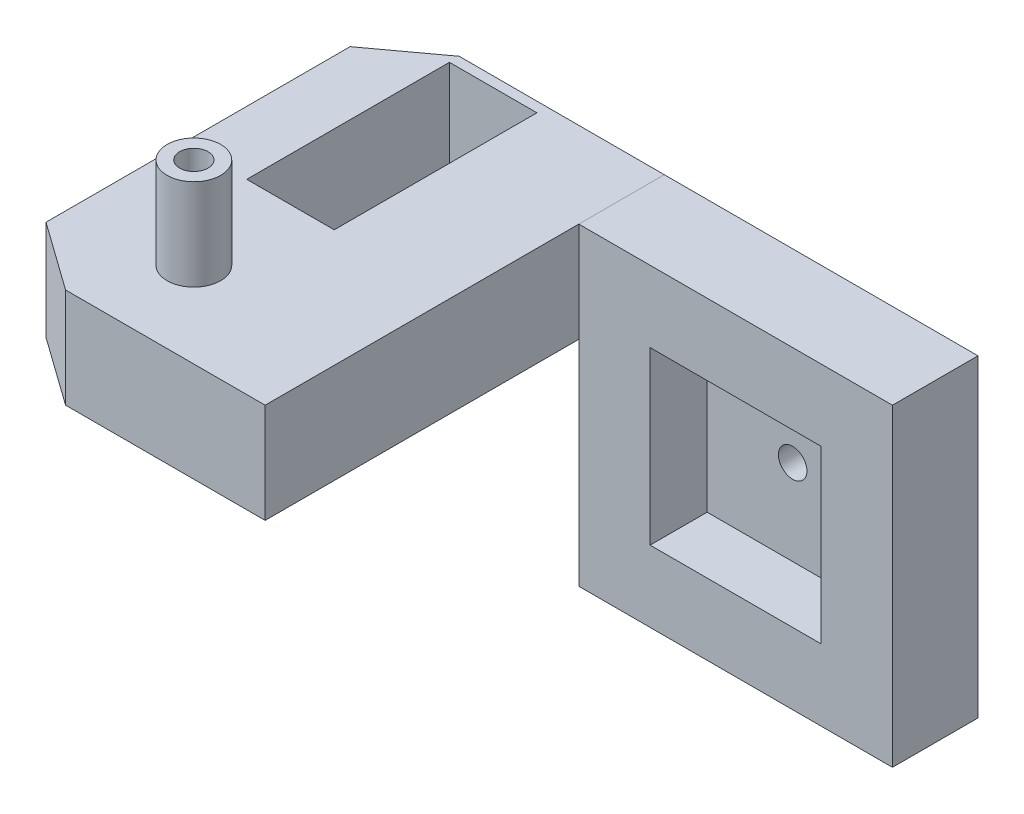
SolidWorks part; units mm, degrees
ref_plane "Front Plane" through (0, 0, 0) normal (0, 0, 1) x (1, 0, 0)
ref_plane "Top Plane" through (0, 0, 0) normal (0, 1, 0) x (1, 0, 0)
ref_plane "Right Plane" through (0, 0, 0) normal (1, 0, 0) x (0, 0, -1)
sketch "Sketch1" plane through (0, 0, 0) normal (0, 0, 1) x (1, 0, 0)
  line L0 (-28.7496, 4.3597) -> (1.2504, -25.6403) construction
  line L5 (-41.2496, 16.8597) -> (13.7504, 16.8597)
  line L6 (-41.2496, 16.8597) -> (-41.2496, -38.1403)
  line L7 (-41.2496, -38.1403) -> (13.7504, -38.1403)
  line L8 (13.7504, 16.8597) -> (13.7504, -38.1403)
  line L9 (-28.7496, 4.3597) -> (1.2504, 4.3597)
  line L10 (-28.7496, 4.3597) -> (-28.7496, -25.6403)
  line L11 (-28.7496, -25.6403) -> (1.2504, -25.6403)
  line L12 (1.2504, 4.3597) -> (1.2504, -25.6403)
  line L13 (-41.2496, 16.8597) -> (13.7504, -38.1403)
  point P10 (-13.7496, -10.6403)
  point P11 (-13.7496, -10.6403)
  dimension "D1" = 55
  dimension "D2" = 30
extrude "Boss-Extrude1" add sketch "Sketch1" along normal blind 15 contours L13 L6 L7 L11 L10 | L5 L13 L9 L12 L8
ref_plane "Plane1" through (0, -10.6403, 0) normal (0, 1, 0) x (1, 0, 0)
sketch "Sketch5" plane through (0, 16.8597, 0) normal (0, 1, 0) x (1, 0, 0)
  line L1 (-41.2496, 0) -> (-111.2496, 0)
  line L2 (-41.2496, 0) -> (-41.2496, -70)
  line L3 (-41.2496, -70) -> (-111.2496, -70)
  line L4 (-111.2496, 0) -> (-111.2496, -70)
  dimension "D1" = 70
extrude "Boss-Extrude4" add sketch "Sketch5" against normal blind 17.5 separate body
sketch "Sketch6" plane through (0, 16.8597, 0) normal (0, 1, 0) x (1, 0, 0)
  line L0 (-111.2496, 0) -> (-111.2496, -25)
  line L1 (-111.2496, 0) -> (-111.2496, -70) construction
  line L2 (-111.2496, -25) -> (-77.2206, 0)
  line L3 (-41.2496, 0) -> (-111.2496, 0) construction
  line L4 (-77.2206, 0) -> (-111.2496, 0)
  line L5 (-111.2496, -45) -> (-76.2496, -70)
  line L6 (-111.2496, -70) -> (-41.2496, -70) construction
  line L7 (-76.2496, -70) -> (-111.2496, -70)
  line L8 (-111.2496, -70) -> (-111.2496, -45)
  line L9 (-88.2496, -8.1027) -> (-88.2496, -61.4286)
  line L10 (-88.2496, -61.4286) -> (-111.2496, -45)
  line L11 (-111.2496, -25) -> (-88.2496, -8.1027)
  line L12 (-111.2496, -45) -> (-111.2496, -25)
  line L13 (-88.2496, -61.4286) -> (-111.2496, -45)
  point P16 (-111.2496, -35)
  point P17 (-88.2496, -34.7656)
  line M9 (-111.2496, 0) -> (-111.2496, -70)
  dimension "D1" = 25
  dimension "D2" = 23
extrude "Cut-Extrude1" cut sketch "Sketch6" against normal through all contours L9 L2 L5 M9
sketch "Sketch8" plane through (0, 16.8597, 0) normal (0, 1, 0) x (1, 0, 0)
  line L1 (-77.1594, -1.772) -> (-61.825, -1.772)
  line L2 (-77.1594, -1.772) -> (-77.1594, -37.3148)
  line L3 (-77.1594, -37.3148) -> (-61.825, -37.3148)
  line L4 (-61.825, -1.772) -> (-61.825, -37.3148)
extrude "Cut-Extrude3" cut sketch "Sketch8" against normal through all
sketch "Sketch9" plane through (0, 16.8597, 0) normal (0, 1, 0) x (1, 0, 0)
  line L0 (-76.2496, -70) -> (-41.2496, -70) construction
  line L1 (-41.2496, -70) -> (-41.2496, 0) construction
  circle A0 centre (-68.7496, -55) radius 4.7
  dimension "D1" = 9.4
  dimension "D2" = 15
  dimension "D3" = 27.5
extrude "Boss-Extrude5" add sketch "Sketch9" along normal blind 16
sketch "Sketch10" plane through (0, 32.8597, 0) normal (0, 1, 0) x (1, 0, 0)
  circle A0 centre (-68.7496, -55) radius 2.5
  circle A1 centre (-68.7496, -55) radius 4.7 construction
  dimension "D1" = 5
extrude "Cut-Extrude4" cut sketch "Sketch10" against normal blind 10
sketch "Sketch12" plane through (-732.7703, -892.3175, 5) normal (0, 0, 1) x (1, 0, 0)
  line L1 (704.0207, 896.6773) -> (734.0207, 896.6773)
  line L2 (704.0207, 896.6773) -> (704.0207, 866.6773)
  line L3 (704.0207, 866.6773) -> (734.0207, 866.6773)
  line L4 (734.0207, 896.6773) -> (734.0207, 866.6773)
extrude "Boss-Extrude6" add sketch "Sketch12" against normal blind 5
sketch "Sketch13" plane through (0, 0, 5) normal (0, 0, 1) x (1, 0, 0)
  circle A0 centre (-13.7496, -10.6403) radius 2.5
extrude "Cut-Extrude5" cut sketch "Sketch13" against normal through all contours A0
sketch "Sketch14" plane through (0, 0, 70) normal (0, 0, 1) x (1, 0, 0)
  line L0 (-41.2496, -38.1403) -> (13.7504, -38.1403) construction
  line L1 (-112.3634, 35.6637) -> (-29.9954, 35.6637)
  line L2 (-112.3634, 35.6637) -> (-112.3634, -38.1403)
  line L3 (-112.3634, -38.1403) -> (-29.9954, -38.1403)
  line L4 (-29.9954, 35.6637) -> (-29.9954, -38.1403)
  line L5 (13.7504, 16.8597) -> (13.7504, -38.1403) construction
  line L6 (-29.9954, 35.6637) -> (13.7504, 35.6637)
  line L7 (-29.9954, 35.6637) -> (-29.9954, 5.3269)
  line L8 (-29.9954, 5.3269) -> (13.7504, 5.3269)
  line L9 (13.7504, 35.6637) -> (13.7504, 5.3269)
  line L11 (-29.9954, -38.1403) -> (13.7504, -38.1403)
  line L12 (-29.9954, -38.1403) -> (-29.9954, -27.1142)
  line L13 (-29.9954, -27.1142) -> (13.7504, -27.1142)
  line L14 (13.7504, -38.1403) -> (13.7504, -27.1142)
  line L15 (13.7504, -27.1142) -> (2.2997, -27.1142)
  line L16 (13.7504, -27.1142) -> (13.7504, 5.3269)
  line L17 (13.7504, 5.3269) -> (2.2997, 5.3269)
  line L18 (2.2997, -27.1142) -> (2.2997, 5.3269)
